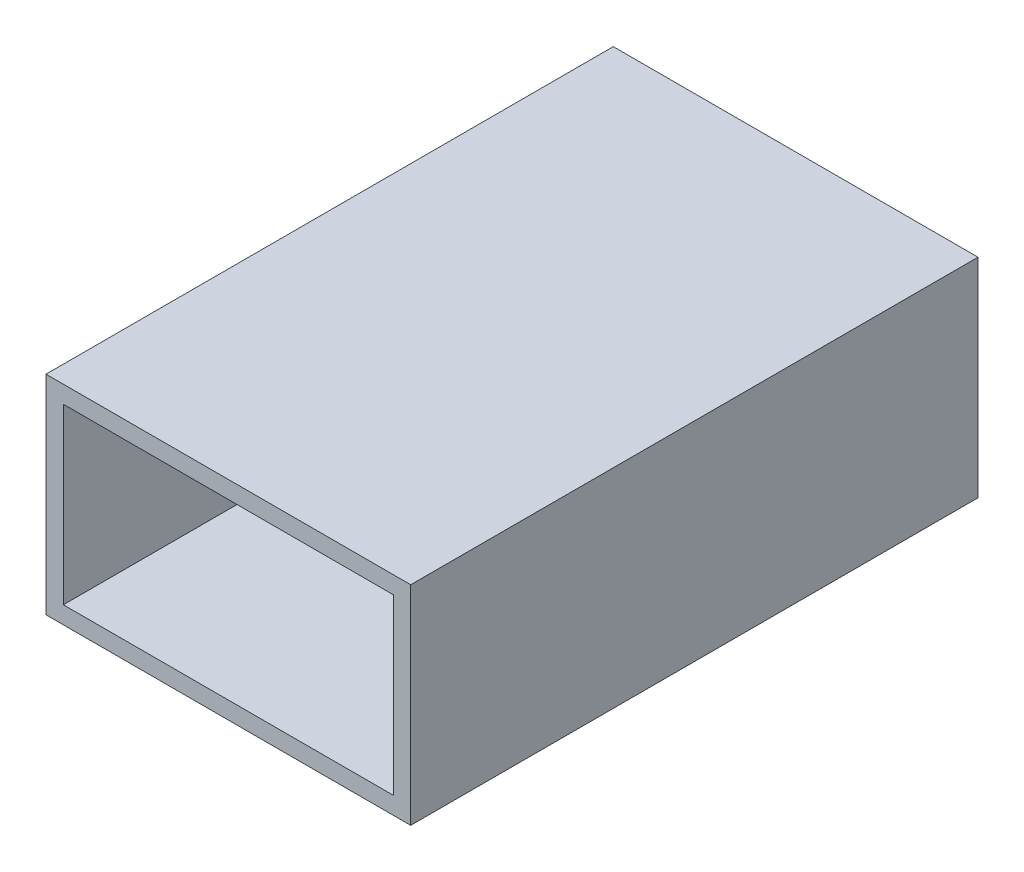
SolidWorks part; units mm, degrees
ref_plane "Front Plane" through (0, 0, 0) normal (0, 0, 1) x (1, 0, 0)
ref_plane "Top Plane" through (0, 0, 0) normal (0, 1, 0) x (1, 0, 0)
ref_plane "Right Plane" through (0, 0, 0) normal (1, 0, 0) x (0, 0, -1)
sketch "Sketch1" plane through (0, 0, 0) normal (0, 0, 1) x (1, 0, 0)
  line L0 (-31.5, 18) -> (31.5, 18)
  line L1 (-28.5, -15) -> (28.5, -15)
  line L2 (-28.5, -15) -> (-28.5, 15)
  line L3 (-28.5, 15) -> (28.5, 15)
  line L4 (28.5, -15) -> (28.5, 15)
  line L5 (-28.5, -15) -> (28.5, 15) construction
  line L6 (-28.5, 15) -> (28.5, -15) construction
  line L7 (31.5, -18) -> (31.5, 18)
  line L8 (-31.5, -18) -> (31.5, -18)
  line L9 (-31.5, -18) -> (-31.5, 18)
  point P0 (0, 0)
  dimension "D1" = 30
  dimension "D2" = 57
  dimension "D3" = 3
extrude "Boss-Extrude1" add sketch "Sketch1" along normal blind 98
sketch "Sketch2" plane through (0, 0, 0) normal (0, 0, -1) x (-1, 0, 0)
  line L1 (-28.5, -15) -> (28.5, -15)
  line L2 (-28.5, -15) -> (-28.5, 15)
  line L3 (-28.5, 15) -> (28.5, 15)
  line L4 (28.5, -15) -> (28.5, 15)
extrude "Boss-Extrude2" add sketch "Sketch2" against normal blind 3
